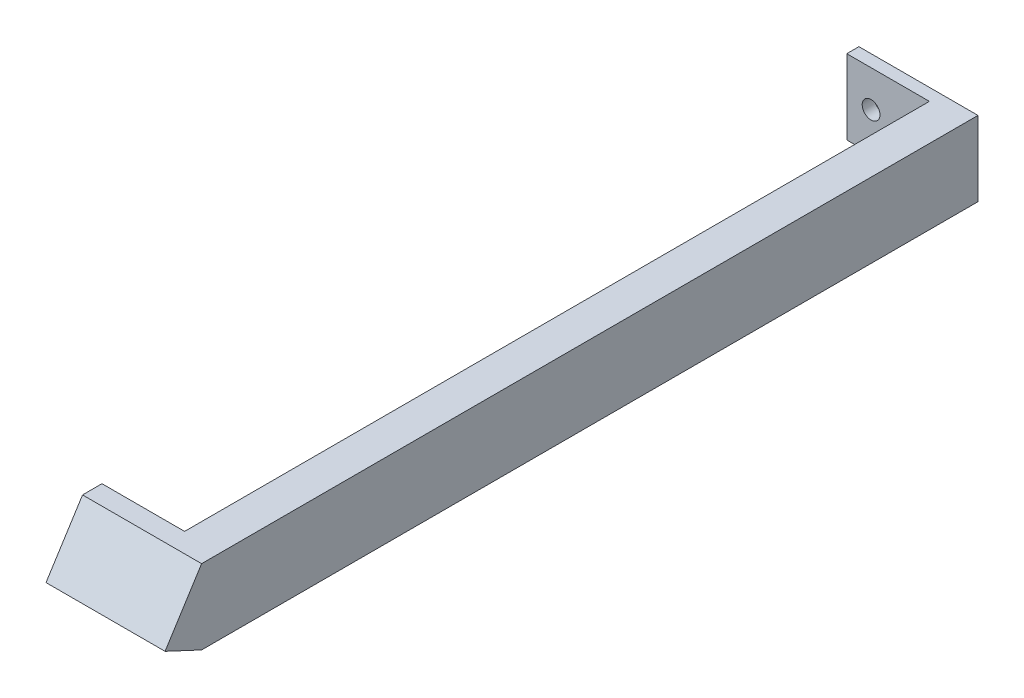
SolidWorks part; units mm, degrees
ref_plane "Front Plane" through (0, 0, 0) normal (0, 0, 1) x (1, 0, 0)
ref_plane "Top Plane" through (0, 0, 0) normal (0, 1, 0) x (1, 0, 0)
ref_plane "Right Plane" through (0, 0, 0) normal (1, 0, 0) x (0, 0, -1)
sketch "Sketch1" plane through (0, 0, 0) normal (1, 0, 0) x (0, 0, -1)
  line L0 (-375.8466, -0.2097) -> (-390.8754, -23.9455)
  line L1 (-56.3743, -0.2097) -> (-375.8466, -0.2097)
  line L2 (-56.3743, -0.2097) -> (-56.3743, -30.9636)
  line L3 (-56.3743, -30.9636) -> (-375.8466, -30.9636)
  line L5 (-390.8754, -23.9455) -> (-375.8466, -30.9636)
  point P6 (0, 0)
  point P11 (0, 0)
  point P12 (0, 0)
  point P13 (0, 0)
  point P14 (0, 0)
  point P15 (0, 0)
  point P16 (0, 0)
extrude "Boss-Extrude1" add sketch "Sketch1" along normal blind 49
sketch "Sketch2" plane through (0, 0, 0) normal (-1, 0, 0) x (0, 0, 1)
  line L0 (375.8466, -30.9636) -> (56.3743, -30.9636) construction
  line L1 (61.3743, -30.9636) -> (367.8466, -30.9636)
  line L2 (61.3743, -30.9636) -> (61.3743, -0.2097)
  line L3 (61.3743, -0.2097) -> (367.8466, -0.2097)
  line L4 (367.8466, -30.9636) -> (367.8466, -0.2097)
  line L5 (56.3743, -0.2097) -> (375.8466, -0.2097) construction
  line L6 (56.3743, -30.9636) -> (56.3743, -0.2097) construction
  dimension "D1" = 5
  dimension "D2" = 8
extrude "Cut-Extrude1" cut sketch "Sketch2" against normal blind 34
sketch "Sketch4" plane through (0, 0, 56.3743) normal (0, 0, -1) x (-1, 0, 0)
  line L0 (-49, -0.2097) -> (0, -0.2097) construction
  line L1 (0, -30.9636) -> (0, -0.2097) construction
  circle A0 centre (-10, -15.2097) radius 3.65
  dimension "D1" = 7.3
  dimension "D2" = 15
  dimension "D3" = 10
extrude "Cut-Extrude2" cut sketch "Sketch4" against normal blind 10
